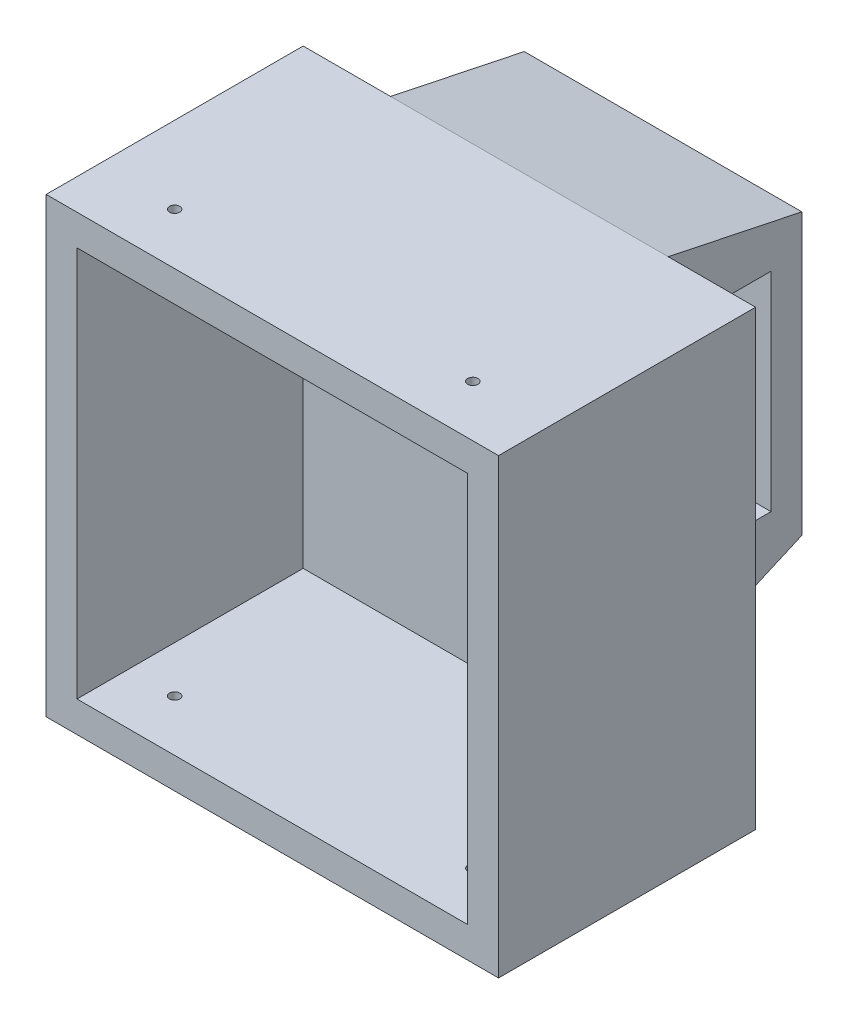
SolidWorks part; units mm, degrees
ref_plane "Plan de face" through (0, 0, 0) normal (0, 0, 1) x (1, 0, 0)
ref_plane "Plan de dessus" through (0, 0, 0) normal (0, 1, 0) x (1, 0, 0)
ref_plane "Plan de droite" through (0, 0, 0) normal (1, 0, 0) x (0, 0, -1)
sketch "Esquisse1" plane through (0, 0, 0) normal (0, 0, 1) x (1, 0, 0)
  line L1 (-41, 35) -> (35, 35)
  line L2 (-41, 35) -> (-41, -41)
  line L3 (-41, -41) -> (35, -41)
  line L4 (35, 35) -> (35, -41)
  dimension "D1" = 76
  dimension "D2" = 76
  dimension "D3" = 35
  dimension "D4" = 35
extrude "Boss.-Extru.1" add sketch "Esquisse1" along normal blind 6
sketch "Esquisse3" plane through (0, -41, 0) normal (0, -1, 0) x (-1, 0, 0)
  line L0 (41, 0) -> (-35, 0)
  line L1 (41, 0) -> (41, -50)
  line L2 (-35, 0) -> (-35, -50)
  line L3 (41, -50) -> (-35, -50)
  dimension "D1" = 50
extrude "Boss.-Extru.2" add sketch "Esquisse3" along normal blind 6
sketch "Esquisse4" plane through (-41, 0, 0) normal (-1, 0, 0) x (0, 0, 1)
  line L0 (0, 35) -> (0, -47)
  line L1 (0, 35) -> (50, 35)
  line L2 (0, -47) -> (50, -47)
  line L3 (50, 35) -> (50, -47)
  line L4 (50, -47) -> (50, -41) construction
extrude "Boss.-Extru.3" add sketch "Esquisse4" along normal blind 6
sketch "Esquisse5" plane through (35, 0, 0) normal (1, 0, 0) x (0, 0, -1)
  line L0 (0, 35) -> (0, -47)
  line L1 (0, 35) -> (-50, 35)
  line L2 (0, -47) -> (-50, -47)
  line L3 (-50, 35) -> (-50, -47)
extrude "Boss.-Extru.4" add sketch "Esquisse5" along normal blind 6
sketch "Esquisse6" plane through (0, 35, 0) normal (0, 1, 0) x (1, 0, 0)
  line L0 (41, 0) -> (-47, 0)
  line L1 (41, 0) -> (41, -50)
  line L2 (-47, 0) -> (-47, -50)
  line L3 (41, -50) -> (-47, -50)
extrude "Boss.-Extru.5" add sketch "Esquisse6" along normal blind 6
sketch "Esquisse8" plane through (0, 0, 0) normal (0, 0, -1) x (-1, 0, 0)
  line L0 (-24, 28.5655) -> (-24, 35.5655)
  line L1 (-24, 28.5655) -> (30, 28.5655)
  line L2 (-24, 35.5655) -> (30, 35.5655)
  line L3 (30, 28.5655) -> (30, 35.5655)
  line L4 (-41, -47) -> (-41, 41) construction
  line L5 (47, 41) -> (47, -47) construction
  dimension "D1" = 54
  dimension "D2" = 7
  dimension "D3" = 17
  dimension "D4" = 17
extrude "Boss.-Extru.6" add sketch "Esquisse8" along normal blind 26
sketch "Esquisse9" plane through (0, 28.5655, 0) normal (0, -1, 0) x (-1, 0, 0)
  line L0 (30, 26) -> (30, 0) construction
  line L1 (-24, 26) -> (30, 26)
  line L2 (-24, 26) -> (-24, 20)
  line L3 (-24, 20) -> (30, 20)
  line L4 (30, 26) -> (30, 20)
  dimension "D1" = 6
extrude "Boss.-Extru.7" add sketch "Esquisse9" along normal blind 40.5
sketch "Esquisse11" plane through (0, 0, -26) normal (0, 0, -1) x (-1, 0, 0)
  line L0 (30, -11.9345) -> (30, 35.5655) construction
  line L1 (-24, -11.9345) -> (30, -11.9345)
  line L2 (-24, -11.9345) -> (-24, -18.9345)
  line L3 (-24, -18.9345) -> (30, -18.9345)
  line L4 (30, -11.9345) -> (30, -18.9345)
  dimension "D1" = 7
extrude "Boss.-Extru.8" add sketch "Esquisse11" against normal blind 26
sketch "Esquisse12" plane through (24, 0, 0) normal (1, 0, 0) x (0, 0, -1)
  line L0 (26, -18.9345) -> (0, -18.9345)
  line L1 (0, -18.9345) -> (0, -30.3645)
  line L2 (0, -30.3645) -> (26, -18.9345)
  line L3 (0, 35.5655) -> (26, 35.5655)
  line L4 (26, 35.5655) -> (0, 41)
  line L5 (0, 41) -> (0, 35.5655)
  dimension "D1" = 5.4345
  dimension "D2" = 11.43
extrude "Boss.-Extru.10" add sketch "Esquisse12" against normal blind 54
sketch "Esquisse13" plane through (0, -47, 0) normal (0, -1, 0) x (-1, 0, 0)
  line L0 (-53.4463, -40) -> (85.0338, -40) construction
  line L1 (-41, -50) -> (47, -50) construction
  line L2 (-41, -50) -> (-41, 0) construction
  line L3 (47, 0) -> (47, -50) construction
  circle A0 centre (-26, -40) radius 1
  circle A1 centre (32, -40) radius 1
  dimension "D2" = 2
  dimension "D3" = 2
  dimension "D4" = 15
  dimension "D5" = 15
  dimension "D1" = 10
extrude "Enlèv. mat.-Extru.1" cut sketch "Esquisse13" against normal blind 100
